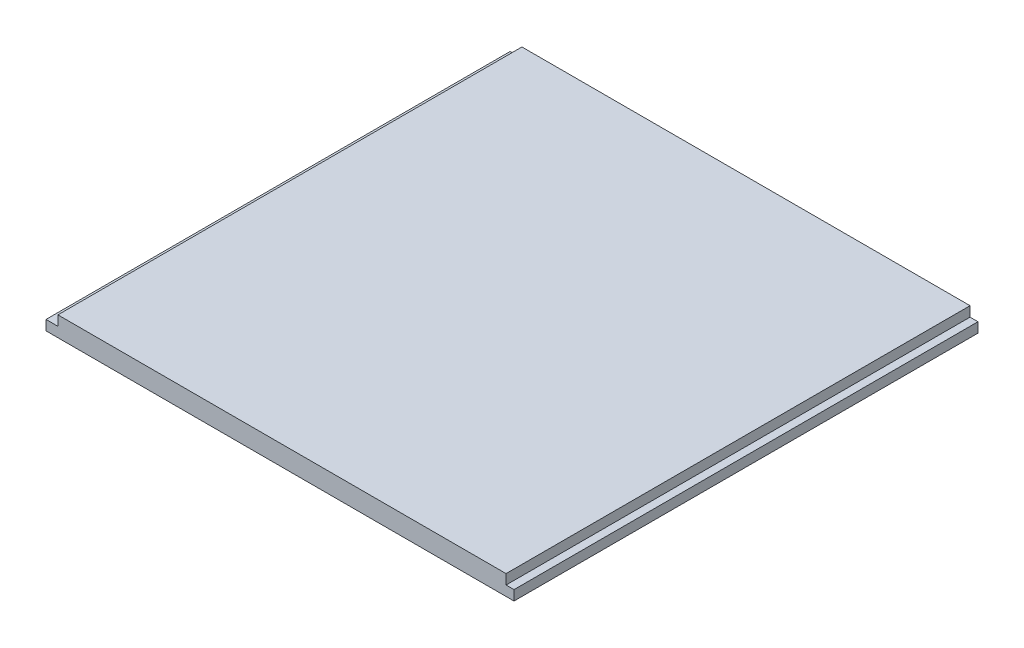
SolidWorks part; units mm, degrees
ref_plane "前视基准面" through (0, 0, 0) normal (0, 0, 1) x (1, 0, 0)
ref_plane "上视基准面" through (0, 0, 0) normal (0, 1, 0) x (1, 0, 0)
ref_plane "右视基准面" through (0, 0, 0) normal (1, 0, 0) x (0, 0, -1)
sketch "草图1" plane through (0, 0, 0) normal (0, 0, 1) x (1, 0, 0)
  line L1 (-37.0032, -29.9419) -> (80.9968, -29.9419)
  line L2 (-37.0032, -29.9419) -> (-37.0032, -27.4419)
  line L3 (-37.0032, -27.4419) -> (80.9968, -27.4419)
  line L4 (80.9968, -29.9419) -> (80.9968, -27.4419)
  line L5 (-34.0032, -27.4419) -> (78.9968, -27.4419)
  line L6 (-34.0032, -27.4419) -> (-34.0032, -24.9419)
  line L7 (-34.0032, -24.9419) -> (78.9968, -24.9419)
  line L8 (78.9968, -27.4419) -> (78.9968, -24.9419)
  dimension "D1" = 118
  dimension "D2" = 2.5
  dimension "D3" = 3
  dimension "D4" = 2.5
  dimension "D5" = 113
extrude "凸台-拉伸1" add sketch "草图1" along normal blind 117 contours L7 L8 L5 L6 | L1 L4 L3 L2
